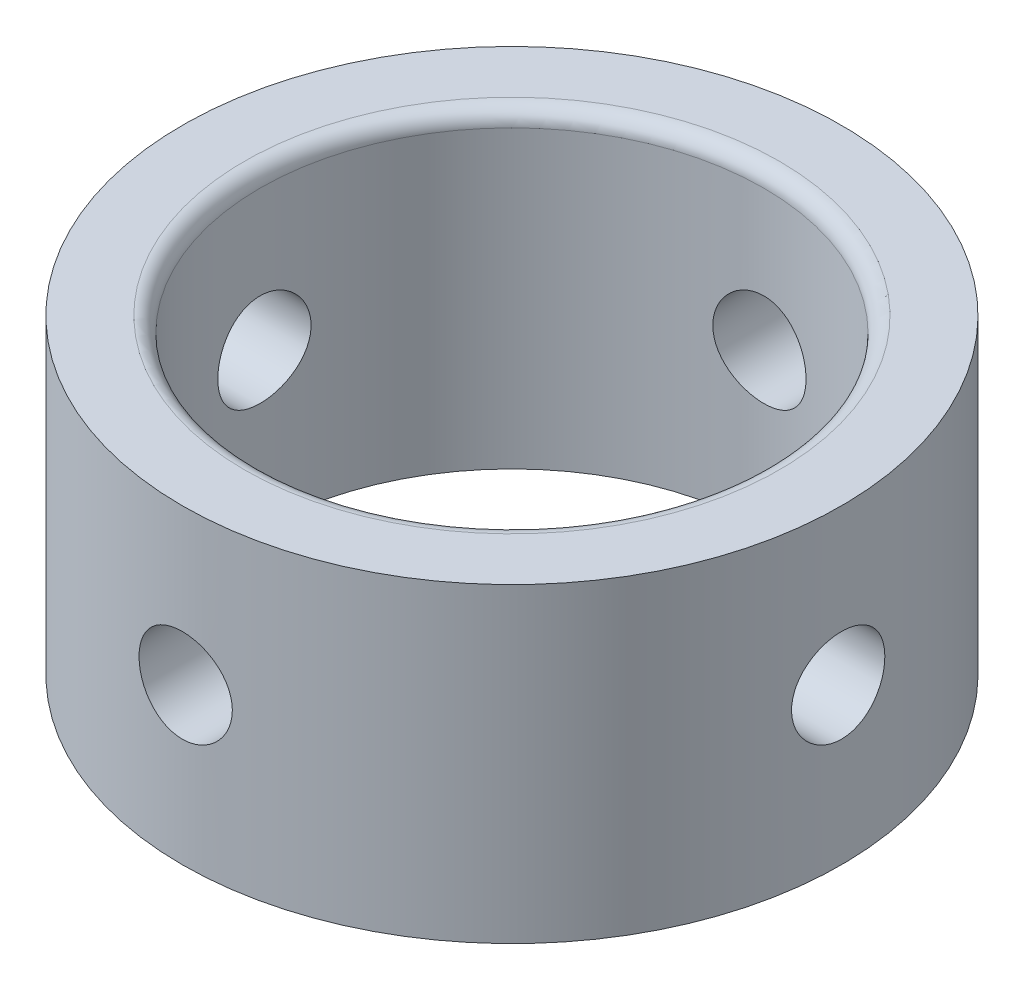
SolidWorks part; units mm, degrees
ref_plane "Front Plane" through (0, 0, 0) normal (0, 0, 1) x (1, 0, 0)
ref_plane "Top Plane" through (0, 0, 0) normal (0, 1, 0) x (1, 0, 0)
ref_plane "Right Plane" through (0, 0, 0) normal (1, 0, 0) x (0, 0, -1)
sketch "Sketch1" plane through (0, 0, 0) normal (0, 1, 0) x (1, 0, 0)
  circle A0 centre (0, 0) radius 16.2
  circle A1 centre (0, 0) radius 21.2
  dimension "D1" = 32.4
  dimension "D2" = 5
extrude "Boss-Extrude1" add sketch "Sketch1" along normal blind 20
fillet "Fillet1" radius 1 1 edges at (0, 20, 16.2)
ref_plane "Plane1" through (21.2, 0, 0) normal (1, 0, 0) x (0, 0, -1)
sketch "Sketch2" plane through (21.2, 0, 0) normal (1, 0, 0) x (0, 0, -1)
  line L0 (0, 20) -> (0, 0) construction
  line L1 (21.2, 20) -> (-21.2, 20) construction
  circle A0 centre (0, 10) radius 3
  dimension "D1" = 6
extrude "Cut-Extrude1" cut sketch "Sketch2" against normal blind 10
ref_axis "Axis1" through (0, 19, 0) along (0, -1, 0)
pattern_circular "CirPattern1" count 4 over 360 about axis through (0, 19, 0) along (0, -1, 0) of "Cut-Extrude1"
